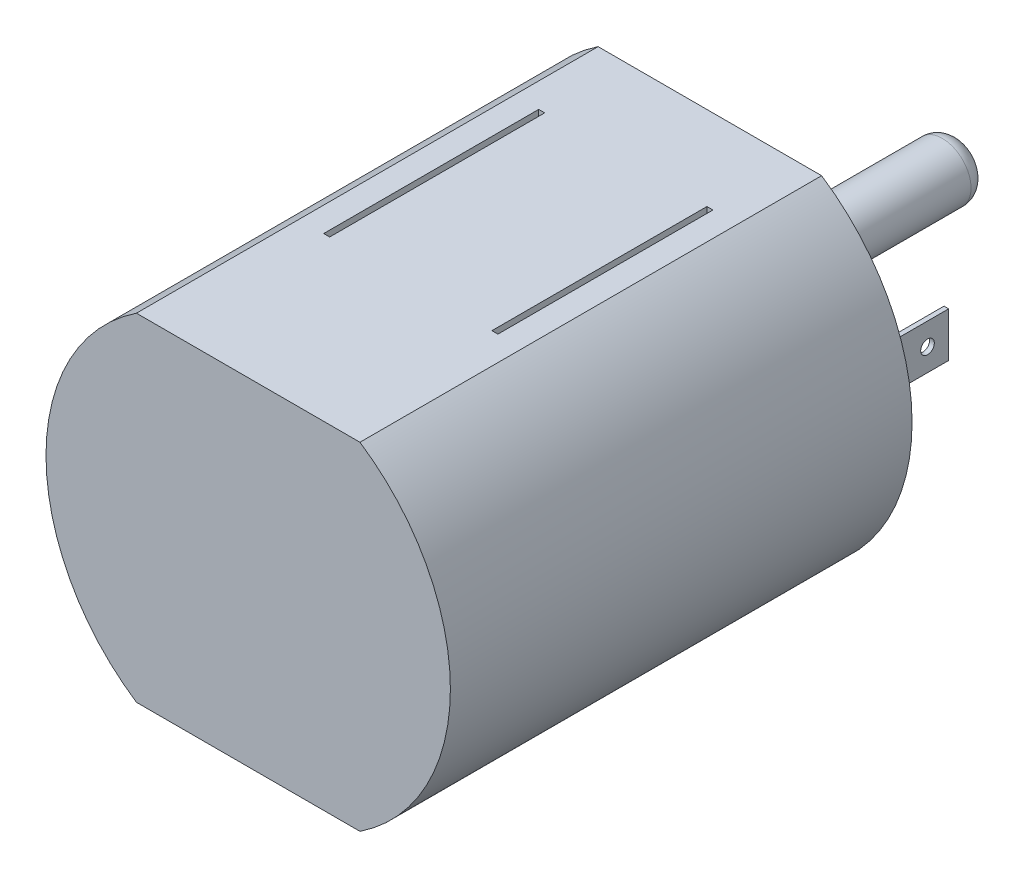
SolidWorks part; units mm, degrees
ref_plane "Front Plane" through (0, 0, 0) normal (0, 0, 1) x (1, 0, 0)
ref_plane "Top Plane" through (0, 0, 0) normal (0, 1, 0) x (1, 0, 0)
ref_plane "Right Plane" through (0, 0, 0) normal (1, 0, 0) x (0, 0, -1)
sketch "Sketch1" plane through (0, 0, 0) normal (0, 0, 1) x (1, 0, 0)
  line L1 (-3.3166, -5) -> (3.3166, -5)
  line L3 (-3.3166, 5) -> (3.3166, 5)
  arc A0 (-3.3166, 5) -> (-3.3166, -5) centre (0, 0) ccw
  arc A1 (3.3166, -5) -> (3.3166, 5) centre (0, 0) ccw
  dimension "D1" = 12
extrude "Boss-Extrude1" add sketch "Sketch1" along normal blind 13.7
sketch "Sketch3" plane through (0, 5, 0) normal (0, 1, 0) x (1, 0, 0)
  line L0 (-2.4067, -8.8749) -> (-2.5852, -8.8749)
  line L2 (-2.4067, -2.494) -> (-2.5852, -2.494)
  line L3 (2.5852, -8.8749) -> (2.4067, -8.8749)
  line L7 (-2.5852, -2.494) -> (-2.5852, -8.8749)
  line L10 (-2.4067, -2.494) -> (-2.4067, -8.8749)
  line L16 (2.5852, -2.494) -> (2.4067, -2.494)
  line L26 (2.4067, -2.494) -> (2.4067, -8.8749)
  line L27 (2.5852, -2.494) -> (2.5852, -8.8749)
  point P0 (0, 0)
  point P9 (0, 0)
extrude "Cut-Extrude1" cut sketch "Sketch3" against normal blind 0.2
sketch "Sketch4" plane through (0, 0, 0) normal (0, 0, -1) x (-1, 0, 0)
  circle A0 centre (0, 0) radius 0.85 construction
  circle A1 centre (0, 0) radius 0.85
extrude "Boss-Extrude3" add sketch "Sketch4" along normal blind 7.4
sketch "Sketch5" plane through (0, 0, 0) normal (0, 0, -1) x (-1, 0, 0)
  line L0 (4.2866, 0.6646) -> (4.1485, -0.6646) construction
  line L2 (4.2866, -0.6646) -> (4.1485, 0.6646) construction
  line L3 (-4.2866, -0.6646) -> (-4.1485, -0.6646)
  line L4 (-4.2866, -0.6646) -> (-4.2866, 0.6646)
  line L5 (-4.2866, 0.6646) -> (-4.1485, 0.6646)
  line L6 (-4.1485, -0.6646) -> (-4.1485, 0.6646)
  line L7 (-4.2866, -0.6646) -> (-4.1485, 0.6646) construction
  line L8 (-4.2866, 0.6646) -> (-4.1485, -0.6646) construction
  line L9 (4.1485, -0.6646) -> (4.1485, 0.6646)
  line L10 (4.2866, 0.6646) -> (4.1485, 0.6646)
  line L11 (4.2866, -0.6646) -> (4.2866, 0.6646)
  line L12 (4.2866, -0.6646) -> (4.1485, -0.6646)
extrude "Boss-Extrude4" add sketch "Sketch5" along normal blind 2.8
sketch "Sketch6" plane through (-4.2866, 0, 0) normal (-1, 0, 0) x (0, 0, 1)
  circle A0 centre (-2.1717, 0) radius 0.202
extrude "Cut-Extrude2" cut sketch "Sketch6" against normal blind 9.6
fillet "Redondeo1" radius 0.5 1 edges at (-0.85, 0, -7.4)
